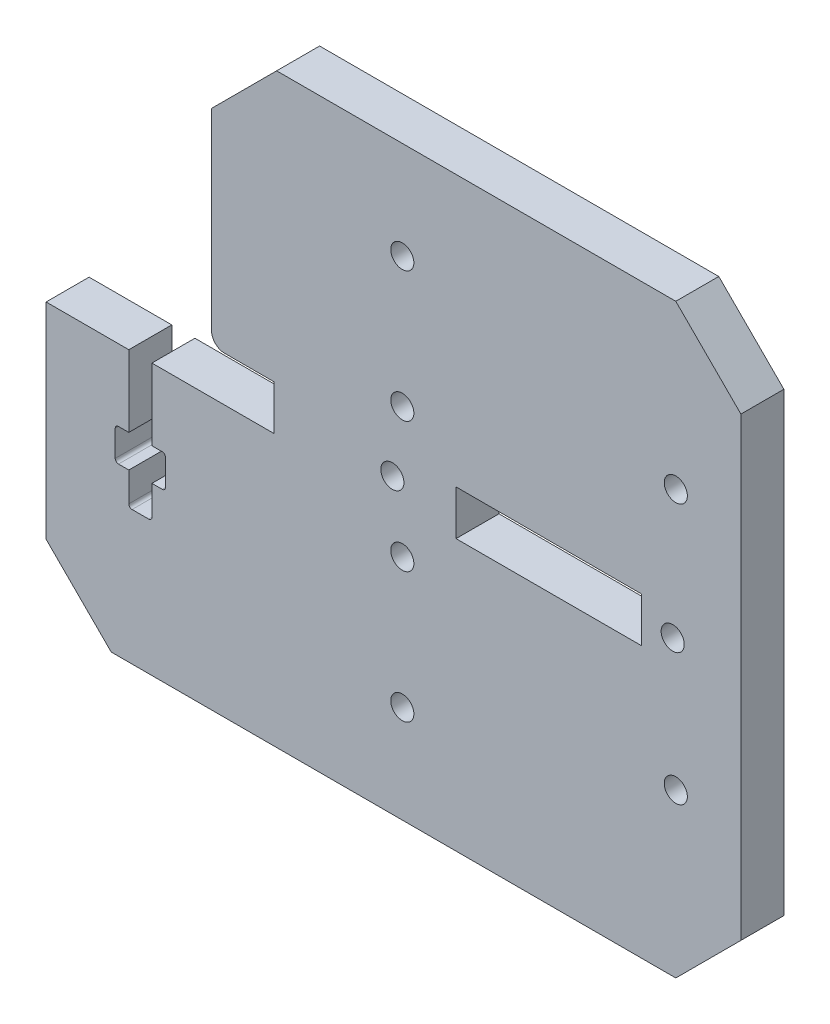
SolidWorks part; units mm, degrees
ref_plane "Front Plane" through (0, 0, 0) normal (0, 0, 1) x (1, 0, 0)
ref_plane "Top Plane" through (0, 0, 0) normal (0, 1, 0) x (1, 0, 0)
ref_plane "Right Plane" through (0, 0, 0) normal (1, 0, 0) x (0, 0, -1)
sketch "Model" plane through (0, 0, 0) normal (0, 0, 1) x (1, 0, 0)
  line L0 (15.75, -3.44) -> (15.75, 3.44)
  line L1 (15.75, 3.44) -> (-12.75, 3.44)
  line L2 (-12.75, 3.44) -> (-12.75, -3.44)
  line L3 (-12.75, -3.44) -> (15.75, -3.44)
  line L4 (-40.3, 45) -> (-50.3, 35)
  line L5 (31, 35) -> (21, 45)
  line L6 (21, -45) -> (31, -35)
  line L7 (-75.7, -35) -> (-65.7, -45)
  line L8 (-75.7, -3.44) -> (-75.7, -35)
  line L9 (-63, -14.44) -> (-64.585, -14.44)
  line L10 (-65.085, -14.94) -> (-65.085, -18.94)
  line L11 (-64.585, -19.44) -> (-63, -19.44)
  line L12 (-63, -19.44) -> (-63, -23.94)
  line L13 (-62.5, -24.44) -> (-59.95, -24.44)
  line L14 (-59.45, -23.94) -> (-59.45, -19.44)
  line L15 (-59.45, -19.44) -> (-57.865, -19.44)
  line L16 (-57.365, -18.94) -> (-57.365, -14.94)
  line L17 (-57.865, -14.44) -> (-59.45, -14.44)
  line L18 (-40.7, -3.44) -> (-59.45, -3.44)
  line L19 (-40.7, -3.44) -> (-40.7, 3.44)
  line L20 (-40.7, 3.44) -> (-48.3, 3.44)
  line L21 (-50.3, 35) -> (-50.3, 5.44)
  line L22 (-65.7, -45) -> (21, -45)
  line L23 (21, 45) -> (-40.3, 45)
  line L24 (31, -35) -> (31, 35)
  line L25 (-63, -3.44) -> (-75.7, -3.44)
  line L26 (-59.45, -14.44) -> (-59.45, -3.44)
  line L27 (-63, -3.44) -> (-63, -14.44)
  circle A0 centre (-21, 30) radius 1.775
  circle A1 centre (-21, 10) radius 1.775
  circle A2 centre (-21, -10) radius 1.775
  circle A3 centre (-21, -30) radius 1.775
  circle A4 centre (21, 20) radius 1.775
  circle A5 centre (21, -20) radius 1.775
  circle A6 centre (-22.525, 0) radius 1.775
  circle A7 centre (20.525, 0) radius 1.775
  arc A8 (-64.585, -14.44) -> (-65.085, -14.94) centre (-64.585, -14.94) ccw
  arc A9 (-65.085, -18.94) -> (-64.585, -19.44) centre (-64.585, -18.94) ccw
  arc A10 (-63, -23.94) -> (-62.5, -24.44) centre (-62.5, -23.94) ccw
  arc A11 (-59.95, -24.44) -> (-59.45, -23.94) centre (-59.95, -23.94) ccw
  arc A12 (-57.865, -19.44) -> (-57.365, -18.94) centre (-57.865, -18.94) ccw
  arc A13 (-57.365, -14.94) -> (-57.865, -14.44) centre (-57.865, -14.94) ccw
  arc A14 (-50.3, 5.44) -> (-48.3, 3.44) centre (-48.3, 5.44) ccw
extrude "Boss-Extrude1" add sketch "Model" along normal blind 6.6
